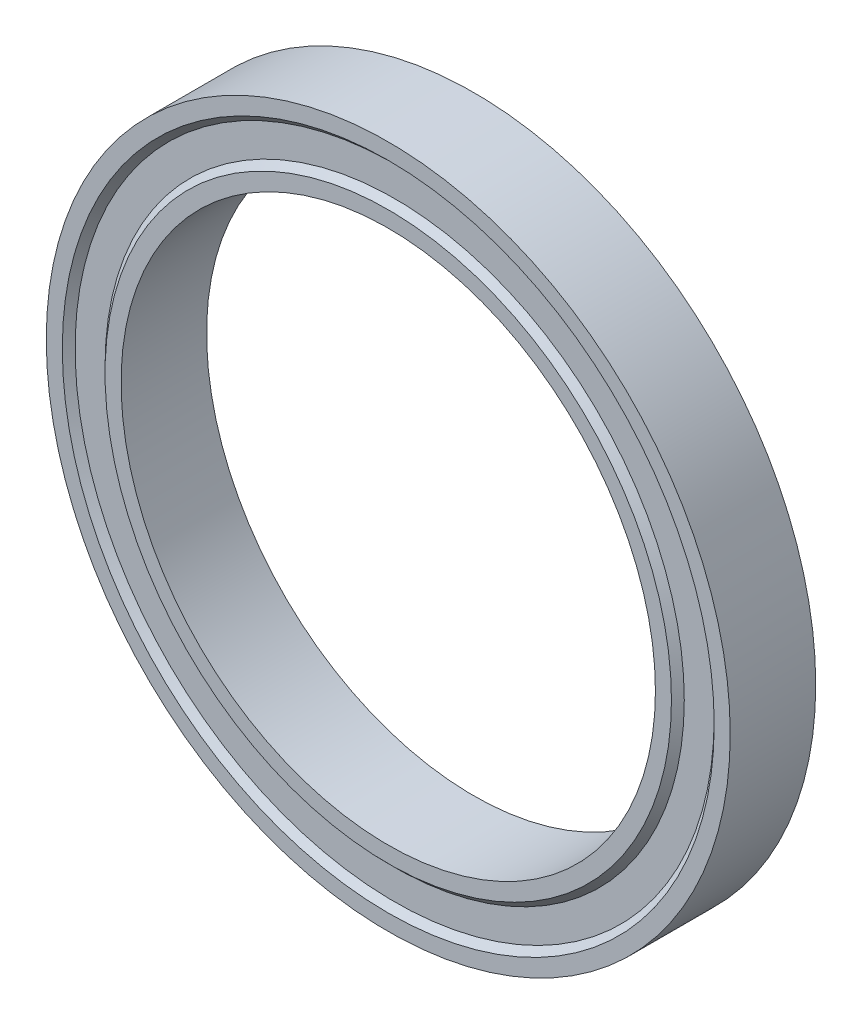
SolidWorks part; units mm, degrees
ref_plane "Front Plane" through (0, 0, 0) normal (0, 0, 1) x (1, 0, 0)
ref_plane "Top Plane" through (0, 0, 0) normal (0, 1, 0) x (1, 0, 0)
ref_plane "Right Plane" through (0, 0, 0) normal (1, 0, 0) x (0, 0, -1)
sketch "Sketch1" plane through (0, 0, 0) normal (0, 1, 0) x (1, 0, 0)
  line L0 (0, 0) -> (12.5, 0) construction
  line L1 (12.5, -2) -> (12.5, 2)
  line L2 (12.5, 2) -> (13.25, 2)
  line L3 (13.25, 2) -> (13.55, 1.7)
  line L4 (13.55, 1.7) -> (14.95, 1.7)
  line L5 (14.95, 1.7) -> (15.25, 2)
  line L6 (15.25, 2) -> (16, 2)
  line L7 (16, 2) -> (16, -2)
  line L8 (16, 0) -> (12.5, 0) construction
  line L9 (15.25, -2) -> (16, -2)
  line L10 (14.95, -1.7) -> (15.25, -2)
  line L11 (13.55, -1.7) -> (14.95, -1.7)
  line L12 (13.25, -2) -> (13.55, -1.7)
  line L13 (12.5, -2) -> (13.25, -2)
  line L14 (0, 0) -> (0, 2) construction
  point P9 (0, 0)
  dimension "D1" = 12.5
  dimension "D2" = 16
  dimension "D3" = 2
  dimension "D4" = 0.3
  dimension "D5" = 0.75
revolve "Revolve1" add sketch "Sketch1" angle 360 about L14
